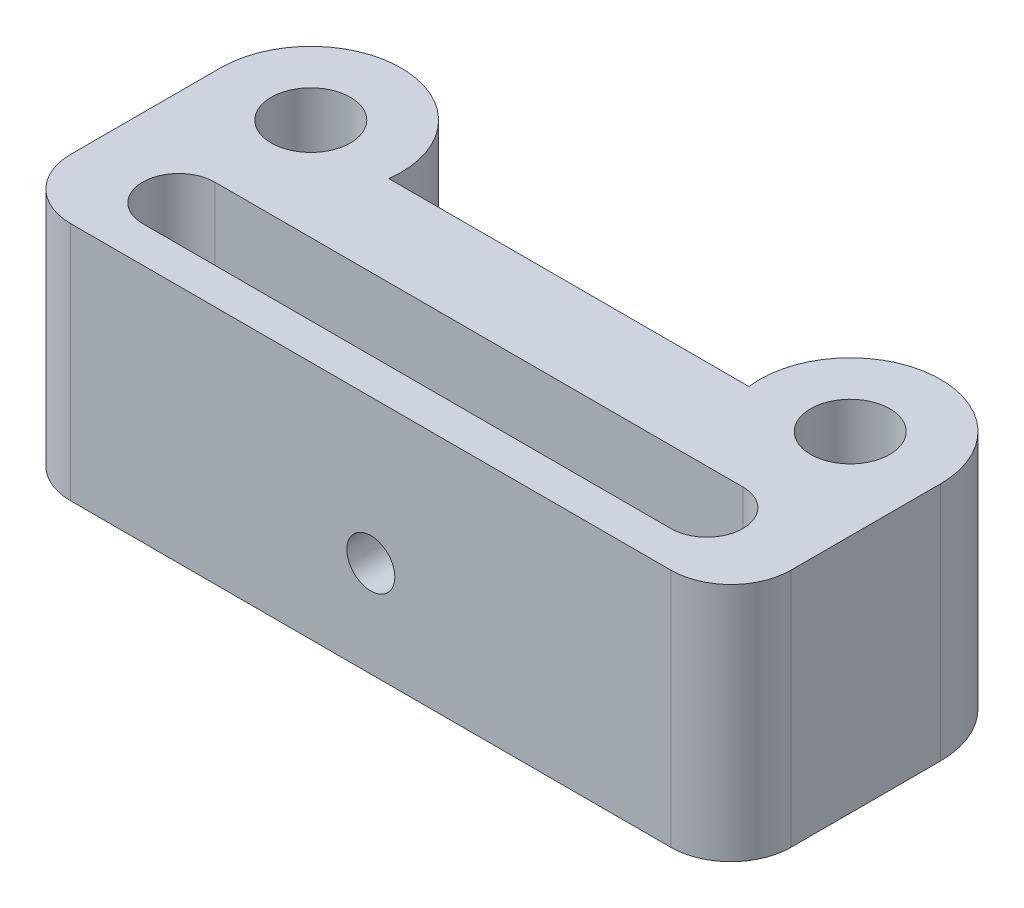
SolidWorks part; units mm, degrees
ref_plane "Front" through (0, 0, 0) normal (0, 0, 1) x (1, 0, 0)
ref_plane "Top" through (0, 0, 0) normal (0, 1, 0) x (1, 0, 0)
ref_plane "Right" through (0, 0, 0) normal (1, 0, 0) x (0, 0, -1)
sketch "Esquisse1" plane through (0, 0, 0) normal (0, 1, 0) x (1, 0, 0)
  line L0 (30, 0) -> (-30, 0)
  line L5 (0, 0) -> (-30, 0) construction
  line L6 (0, 0) -> (0, 25) construction
  line L7 (0, 25) -> (-30, 25) construction
  line L8 (-30, 0) -> (-30, 25) construction
  line L9 (-30, 0) -> (-30, 17.4687)
  line L10 (0, 16.5) -> (-39.5889, 16.5) construction
  line L11 (-15, 16.5) -> (15, 16.5)
  line L12 (30, 0) -> (30, 17.4687)
  line L13 (22, 3) -> (-22, 3)
  line L14 (22, 9) -> (-22, 9)
  arc A1 (-30, 17.4687) -> (-15, 16.5) centre (-22.4687, 17.4687) cw
  arc A2 (30, 17.4687) -> (15, 16.5) centre (22.4687, 17.4687) ccw
  arc A3 (-22, 3) -> (-22, 9) centre (-22, 6) cw
  arc A4 (22, 3) -> (22, 9) centre (22, 6) ccw
  circle A5 centre (-22.4687, 17.4687) radius 3
  circle A6 centre (22.4687, 17.4687) radius 3
  point P20 (0, 3)
  point P22 (0, 9)
  dimension "D8" = 6
  dimension "D1" = 30
  dimension "D2" = 25
  dimension "D3" = 15
  dimension "D4" = 16.5
  dimension "D5" = 3
  dimension "D6" = 6
  dimension "D7" = 22
extrude "Boss.-Extru.1" add sketch "Esquisse1" along normal blind 20
sketch "Esquisse2" plane through (0, 0, 0) normal (0, 0, 1) x (1, 0, 0)
  line L0 (-30, 20) -> (30, 20) construction
  line L1 (0, 0) -> (0, 14.46) construction
  circle A0 centre (0, 8) radius 2
  dimension "D2" = 4
  dimension "D1" = 12
extrude "Enlèv. mat.-Extru.1" cut sketch "Esquisse2" against normal through all
fillet "Congé1" radius 5 2 edges at (30, 10, 0) (-30, 10, 0)
hole_wizard "Dégagement M61" positions "Esquisse3" profile "Esquisse4" hole size "M6" standard "ISO" end condition through all
sketch "Esquisse3" plane through (0, 20, 0) normal (0, 1, 0) x (1, 0, 0)
  point P0 (-22.4687, 17.4687)
  point P3 (22.4687, 17.4687)
sketch "Esquisse4" plane through (-22.4687, 20, -17.4687) normal (1, 0, 0) x (0, 0, 1)
  line L0 (0, 0) -> (0, 20)
  line L1 (0, 20) -> (3.3, 20)
  line L2 (3.3, 20) -> (3.3, 0)
  line L5 (3.3, 0) -> (0, 0)
  line L11 (0, -6.35) -> (0, 107.95) construction
  dimension "Diamètre du perçage jusqu'au prochain" = 6.6
  dimension "Profondeur du perçage jusqu'au prochain" = 20
